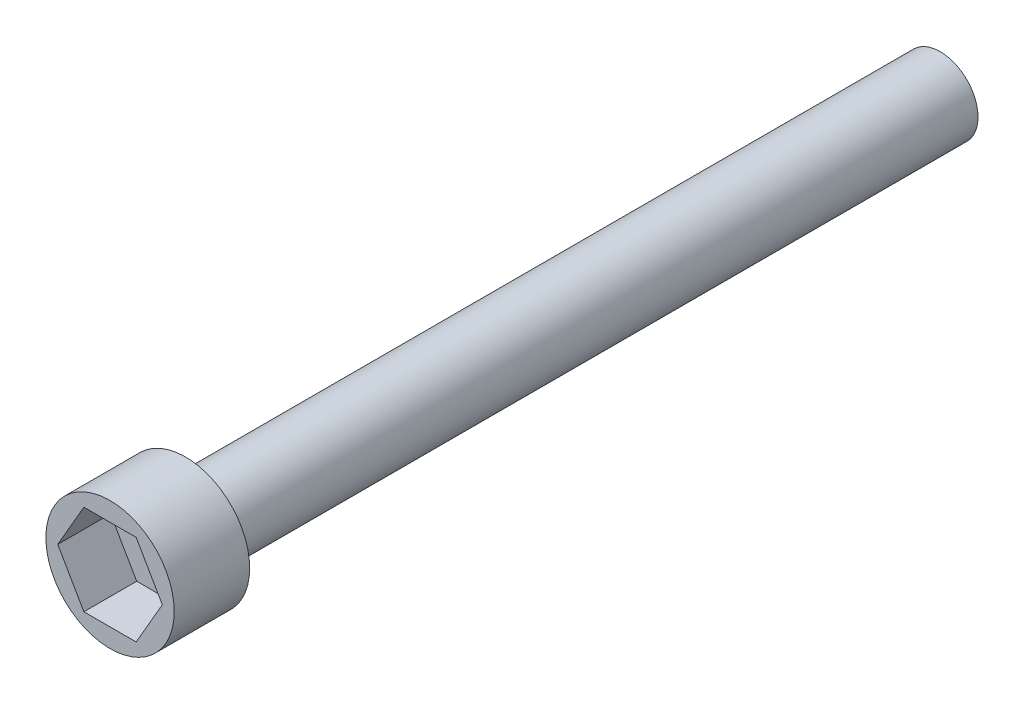
SolidWorks part; units mm, degrees
ref_plane "Plan de face" through (0, 0, 0) normal (0, 0, 1) x (1, 0, 0)
ref_plane "Plan de dessus" through (0, 0, 0) normal (0, 1, 0) x (1, 0, 0)
ref_plane "Plan de droite" through (0, 0, 0) normal (1, 0, 0) x (0, 0, -1)
sketch "Esquisse1" plane through (0, 0, 0) normal (0, 0, 1) x (1, 0, 0)
  circle A0 centre (0, 0) radius 2.5
  dimension "D1" = 5
extrude "Boss.-Extru.1" add sketch "Esquisse1" along normal blind 50
sketch "Esquisse2" plane through (0, 0, 50) normal (0, 0, 1) x (1, 0, 0)
  circle A0 centre (0, 0) radius 4.25
  dimension "D1" = 8.5
extrude "Boss.-Extru.2" add sketch "Esquisse2" along normal blind 5
sketch "Esquisse3" plane through (0, 0, 55) normal (0, 0, 1) x (1, 0, 0)
  line L1 (3.4641, 0) -> (1.7321, 3)
  line L2 (1.7321, 3) -> (-1.7321, 3)
  line L3 (-1.7321, 3) -> (-3.4641, 0)
  line L4 (-3.4641, 0) -> (-1.7321, -3)
  line L5 (-1.7321, -3) -> (1.7321, -3)
  line L6 (1.7321, -3) -> (3.4641, 0)
  circle A0 centre (0, 0) radius 3 construction
  dimension "D1" = 6
extrude "Enlèv. mat.-Extru.1" cut sketch "Esquisse3" against normal blind 3.5
